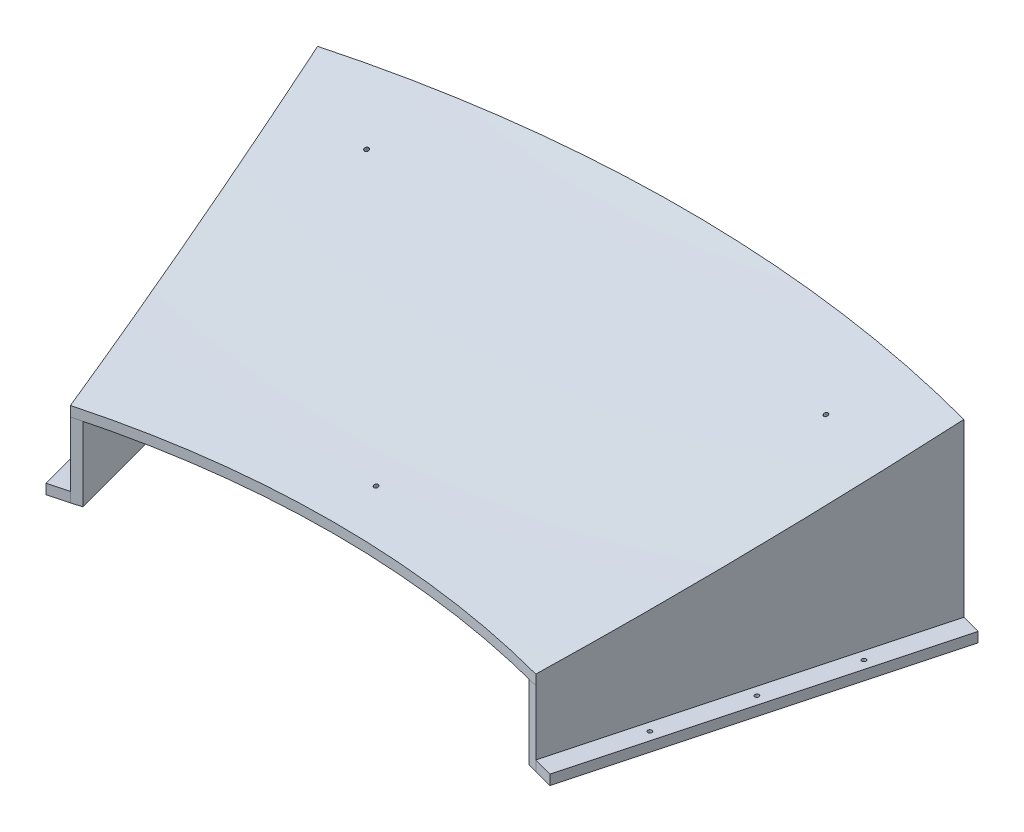
SolidWorks part; units mm, degrees
ref_plane "Спереди" through (0, 0, 0) normal (0, 0, 1) x (1, 0, 0)
ref_plane "Сверху" through (0, 0, 0) normal (0, 1, 0) x (1, 0, 0)
ref_plane "Справа" through (0, 0, 0) normal (1, 0, 0) x (0, 0, -1)
sketch "Эскиз2" plane through (0, 0, 0) normal (1, 0, 0) x (0, 0, -1)
  line L0 (0, 605.2868) -> (0, -166.3215) construction
  line L2 (1250, 181.5625) -> (1250, 171.5625)
  line L3 (900, 74.49) -> (900, 84.49)
  spline S0 degree 2 poles (865, 76.521) (1074.7689, 123.3352) (1284.5379, 192.8548) knots 0 0 0 1 1 1 construction
  spline S1 degree 2 poles (900, 84.49) (1075, 125.125) (1250, 181.5625) knots 0.083425 0.083425 0.083425 0.917676 0.917676 0.917676
  spline S2 degree 2 poles (865, 66.521) (1074.7689, 113.3352) (1284.5379, 182.8548) knots 0 0 0 1 1 1 construction
  spline S3 degree 2 poles (900, 74.49) (1075, 115.125) (1250, 171.5625) knots 0.083425 0.083425 0.083425 0.917676 0.917676 0.917676
  dimension "D1" = 84.49
  dimension "D2" = 900
  dimension "D3" = 1250
  dimension "D4" = 10
revolve "Повернуть1" add sketch "Эскиз2" angle 15 about L0
sketch "Эскиз5" plane through (0, 0, 0) normal (0, 1, 0) x (1, 0, 0)
  line L0 (-323.5238, 1207.4073) -> (-232.9371, 869.3332)
  line L1 (-232.9371, 869.3332) -> (-223.3231, 872.09)
  line L2 (-223.3231, 872.09) -> (-313.8194, 1209.8269)
  line L3 (-313.8194, 1209.8269) -> (-323.5238, 1207.4073)
  line L4 (323.5238, 1207.4073) -> (232.9371, 869.3332)
  line L5 (232.9371, 869.3332) -> (223.3231, 872.09)
  line L6 (223.3231, 872.09) -> (313.8194, 1209.8269)
  line L7 (313.8194, 1209.8269) -> (323.5238, 1207.4073)
  point P10 (0, 0)
  point P13 (0, 0)
  point P15 (0, 0)
  point P16 (0, 0)
  point P17 (0, 0)
  dimension "D1" = 10
  dimension "D2" = 89
  dimension "D3" = 89
  dimension "D4" = 10
  dimension "D5" = 89
  dimension "D6" = 89
extrude "Бобышка-Вытянуть1" add sketch "Эскиз5" along normal up to next
sketch "Эскиз6" plane through (0, 0, 0) normal (-0.9659, 0, 0.2588) x (0.2588, 0, 0.9659)
  line L0 (-1250, 0) -> (-1250, 10)
  line L1 (-1250, 171.5625) -> (-1250, 0) construction
  line L2 (-1250, 10) -> (-900, 10)
  line L3 (-900, 74.49) -> (-900, 0) construction
  line L4 (-900, 10) -> (-900, 0)
  line L5 (-900, 0) -> (-1250, 0)
  dimension "D1" = 10
extrude "Бобышка-Вытянуть2" add sketch "Эскиз6" along normal blind 20
sketch "Эскиз7" plane through (0, 0, 0) normal (0.9659, 0, 0.2588) x (0.2588, 0, -0.9659)
  line L0 (900, 0) -> (900, 10)
  line L1 (900, 74.49) -> (900, 0) construction
  line L2 (900, 10) -> (1250, 10)
  line L3 (1250, 171.5625) -> (1250, 0) construction
  line L4 (1250, 10) -> (1250, 0)
  line L5 (1250, 0) -> (900, 0)
  dimension "D1" = 10
extrude "Бобышка-Вытянуть3" add sketch "Эскиз7" along normal blind 20
sketch "Эскиз8" plane through (0, 0, 0) normal (0, 1, 0) x (1, 0, 0)
  line L0 (-458.8399, 1160) -> (458.8399, 1160) construction
  line L1 (0, 0) -> (-574.6241, 1387.2654) construction
  line L2 (0, 0) -> (575.1289, 1388.4839) construction
  line L3 (0, 0) -> (0, 1411.8233) construction
  line L4 (-367.7129, 940) -> (367.7129, 940) construction
  line L5 (-458.8399, 1160) -> (0, 1160) construction
  line L6 (0, 1160) -> (458.8399, 1160) construction
  point P9 (0, 940)
  point P10 (-229.4199, 1160)
  point P12 (229.4199, 1160)
  dimension "D1" = 22.5
  dimension "D2" = 45
  dimension "D3" = 1160
  dimension "D4" = 940
  dimension "D5" = 20
  dimension "D6" = 20
  dimension "D7" = 20
  dimension "D8" = 20
hole_wizard "Отверстие обработанное метчиком M51" positions "Трехмерный эскиз1" profile "Эскиз9" tap size "M5" standard "ISO" end condition through all
sketch3d "Трехмерный эскиз1"
  line L0 (0, 0, -940) -> (0, 104.275, -940) construction
  line L2 (229.4199, 0, -1160) -> (229.4199, 170.8282, -1160) construction
  line L4 (-229.4199, 0, -1160) -> (-229.4199, 170.8282, -1160) construction
  line L6 (0, 0, -940) -> (0, 93.9844, -940) construction
  line L7 (229.4199, 0, -1160) -> (229.4199, 160.3721, -1160) construction
  line L9 (-229.4199, 0, -1160) -> (-229.4199, 160.3721, -1160) construction
  line L10 (0, 104.275, -940) -> (0, 94.5574, -942.3597) construction
  line L14 (229.4199, 170.8282, -1160) -> (229.9867, 161.2644, -1162.8658) construction
  line L16 (-229.4199, 170.8282, -1160) -> (-229.9867, 161.2644, -1162.8658) construction
  line L22 (0, 0, 0) -> (-268.3285, 0, -1356.7306) construction
  line L25 (-229.9867, 0, -1162.8658) -> (-229.9867, 161.2644, -1162.8658) construction
  line L27 (0, 0, -942.3597) -> (0, 94.5574, -942.3597) construction
  line L28 (0, 0, 0) -> (0, 0, -1411.8233) construction
  line L30 (0, 0, 0) -> (270.5726, 0, -1368.0771) construction
  line L32 (229.9867, 0, -1162.8658) -> (229.9867, 161.2644, -1162.8658) construction
  line L33 (0, 94.5574, -942.3597) -> (0, 93.9844, -940) construction
  line L38 (-229.9867, 161.2644, -1162.8658) -> (-229.4199, 160.3721, -1160) construction
  line L40 (229.9867, 161.2644, -1162.8658) -> (229.4199, 160.3721, -1160) construction
  point P63 (-229.9867, 161.2644, -1162.8658)
  point P76 (0, 94.5574, -942.3597)
  point P85 (229.9867, 161.2644, -1162.8658)
  dimension "D1" = 10
  dimension "D4" = 90
  dimension "D2" = 10
  dimension "D3" = 10
  dimension "D5" = 90
  dimension "D6" = 90
sketch "Эскиз9" plane through (229.9867, 161.2644, -1162.8658) normal (0.6971, -0.1678, 0.6971) x (-0.7147, -0.2395, 0.6571)
  line L0 (0, 0) -> (0, 185.6163)
  line L1 (0, 185.6163) -> (2.1, 185.6163)
  line L2 (2.1, 185.6163) -> (2.1, 0)
  line L5 (2.1, 0) -> (0, 0)
  line L11 (0, -6.35) -> (0, 107.95) construction
  dimension "Диаметр проходного сверла" = 4.2
  dimension "Глубина проходного сверла" = 185.6163
cosmetic thread "Отверстие резьбы1" parameters "D2"=5
cosmetic thread "Отверстие резьбы2" parameters "D2"=5
cosmetic thread "Отверстие резьбы3" parameters "D2"=5
sketch "Эскиз10" plane through (0, 10, 0) normal (0, 1, 0) x (1, 0, 0)
  line L0 (333.1831, 1204.8191) -> (242.5964, 866.7451) construction
  line L1 (342.8423, 1202.2309) -> (323.5238, 1207.4073) construction
  line L2 (252.2557, 864.1569) -> (232.9371, 869.3332) construction
  line L3 (-333.1831, 1204.8191) -> (-242.5964, 866.7451) construction
  line L4 (-342.8423, 1202.2309) -> (-323.5238, 1207.4073) construction
  line L5 (-252.2557, 864.1569) -> (-232.9371, 869.3332) construction
  point P6 (265.2431, 951.2636)
  point P7 (310.5364, 1120.3006)
  point P15 (-310.5364, 1120.3006)
  point P16 (-265.2431, 951.2636)
  point P17 (-287.8897, 1035.7821)
  point P18 (287.8897, 1035.7821)
  dimension "D1" = 87.5
  dimension "D2" = 87.5
  dimension "D3" = 87.5
  dimension "D4" = 87.5
hole_wizard "Отверстие обработанное метчиком M52" positions "Эскиз13" profile "Эскиз14" tap size "M5" standard "ISO" end condition through all
sketch "Эскиз13" plane through (0, 10, 0) normal (0, 1, 0) x (1, 0, 0)
  point P0 (-310.5364, 1120.3006)
  point P3 (-287.8897, 1035.7821)
  point P6 (-265.2431, 951.2636)
  point P9 (310.5364, 1120.3006)
  point P12 (287.8897, 1035.7821)
  point P15 (265.2431, 951.2636)
sketch "Эскиз14" plane through (-310.5364, 10, -1120.3006) normal (1, 0, 0) x (0, 0, 1)
  line L0 (0, 0) -> (0, 10)
  line L1 (0, 10) -> (2.1, 10)
  line L2 (2.1, 10) -> (2.1, 0)
  line L5 (2.1, 0) -> (0, 0)
  line L11 (0, -6.35) -> (0, 107.95) construction
  dimension "Диаметр проходного сверла" = 4.2
  dimension "Глубина проходного сверла" = 10
cosmetic thread "Отверстие резьбы4" parameters "D2"=5
cosmetic thread "Отверстие резьбы5" parameters "D2"=5
cosmetic thread "Отверстие резьбы6" parameters "D2"=5
cosmetic thread "Отверстие резьбы7" parameters "D2"=5
cosmetic thread "Отверстие резьбы8" parameters "D2"=5
cosmetic thread "Отверстие резьбы9" parameters "D2"=5
